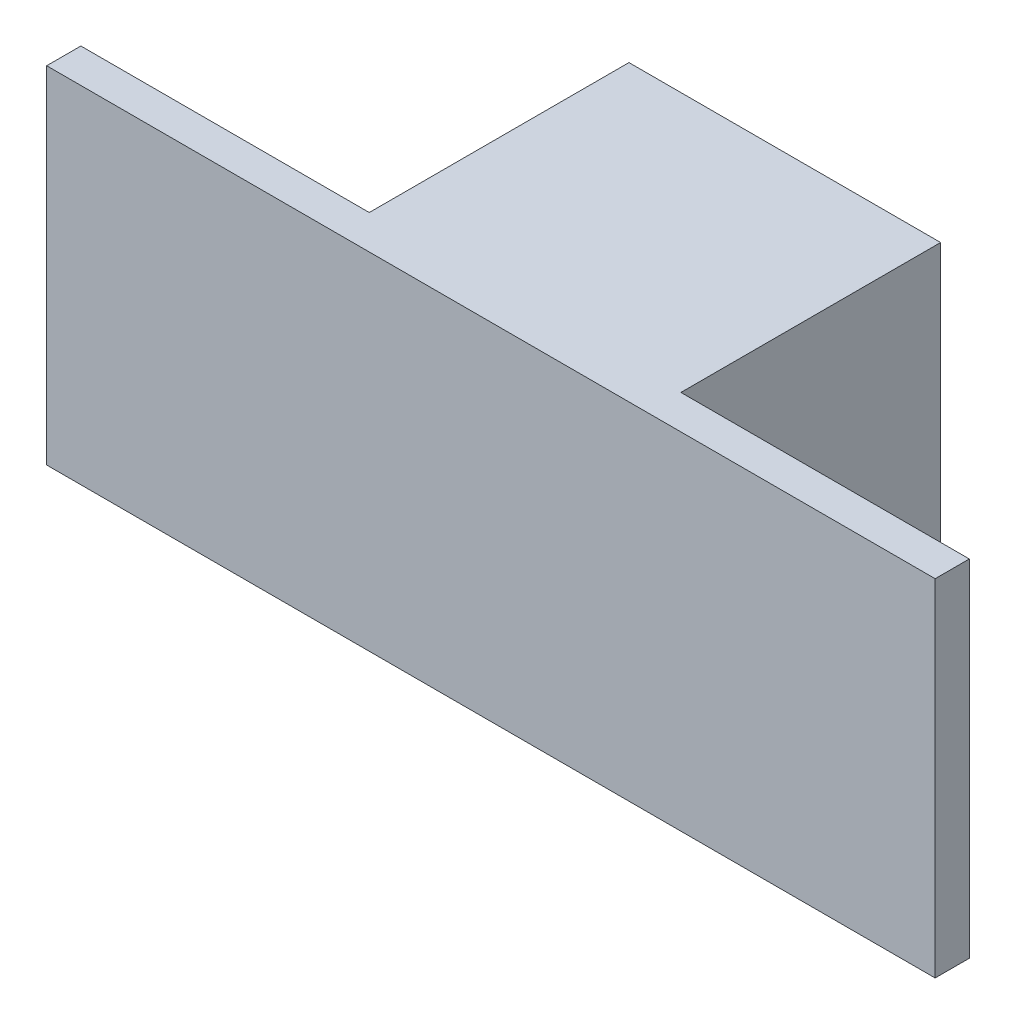
SolidWorks part; units mm, degrees
ref_plane "Front Plane" through (0, 0, 0) normal (0, 0, 1) x (1, 0, 0)
ref_plane "Top Plane" through (0, 0, 0) normal (0, 1, 0) x (1, 0, 0)
ref_plane "Right Plane" through (0, 0, 0) normal (1, 0, 0) x (0, 0, -1)
sketch "Sketch1" plane through (0, 0, 0) normal (0, 0, 1) x (1, 0, 0)
  line L0 (61, 12) -> (-61, 12) construction
  line L1 (-65, 12) -> (65, 12)
  line L2 (-65, 12) -> (-65, -38.6)
  line L3 (-65, -38.6) -> (65, -38.6)
  line L4 (65, 12) -> (65, -38.6)
  line L5 (65, -34.6) -> (65, 8) construction
  line L6 (-65, 8) -> (-65, -34.6) construction
  point P10 (-65, -13.3)
  point P11 (-65, -13.3)
extrude "Boss-Extrude1" add sketch "Sketch1" against normal up to surface (5 mm away)
sketch "Sketch2" plane through (0, 0, -5) normal (0, 0, -1) x (-1, 0, 0)
  line L0 (-65, -38.6) -> (65, -38.6) construction
  line L1 (-22.8, 12) -> (22.8, 12)
  line L2 (-22.8, 12) -> (-22.8, -38.6)
  line L3 (-22.8, -38.6) -> (22.8, -38.6)
  line L4 (22.8, 12) -> (22.8, -38.6)
  line L6 (-65, 12) -> (-65, -38.6) construction
  line L7 (-22.8, -38.6) -> (-22.8, 12) construction
  point P6 (0, -38.6)
  point P7 (0, -38.6)
  point P8 (-65, -13.3)
  point P11 (-22.8, -13.3)
extrude "Boss-Extrude2" add sketch "Sketch2" along normal up to surface (38 mm away)
